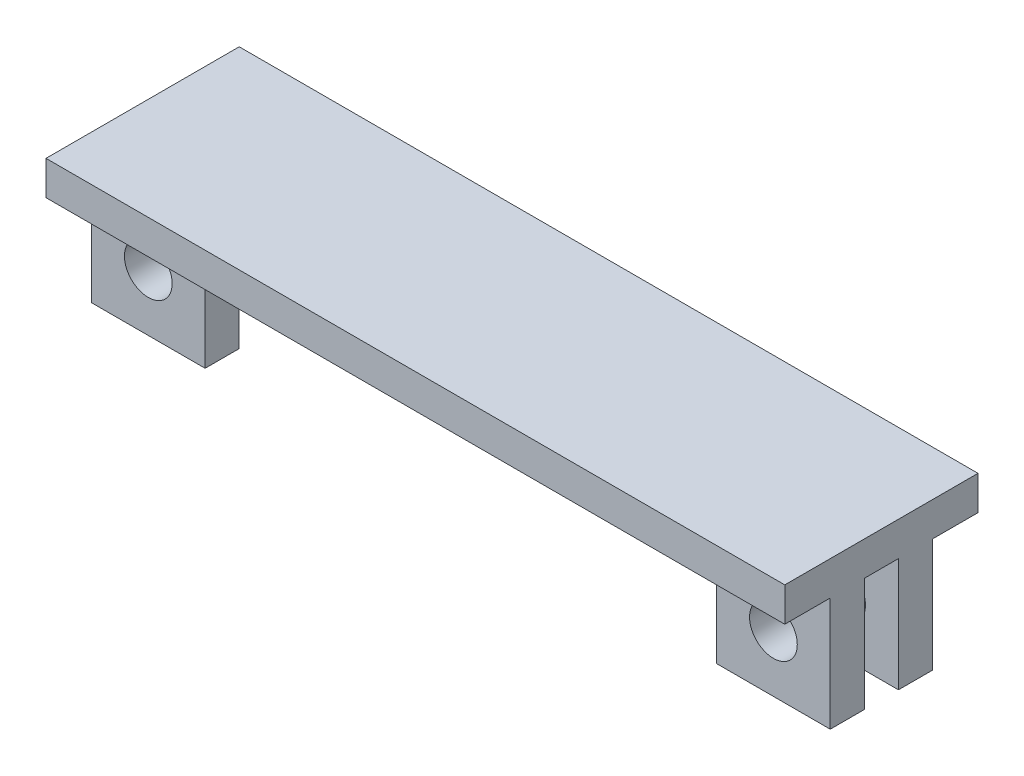
SolidWorks part; units mm, degrees
ref_plane "Спереди" through (0, 0, 0) normal (0, 0, 1) x (1, 0, 0)
ref_plane "Сверху" through (0, 0, 0) normal (0, 1, 0) x (1, 0, 0)
ref_plane "Справа" through (0, 0, 0) normal (1, 0, 0) x (0, 0, -1)
other "Configuration Table"
sketch "Эскиз3" plane through (0, 0, 0) normal (0, 1, 0) x (1, 0, 0)
  line L1 (-5, -1.5) -> (5, -1.5)
  line L2 (-5, -1.5) -> (-5, 1.5)
  line L3 (-5, 1.5) -> (5, 1.5)
  line L4 (5, -1.5) -> (5, 1.5)
  line L5 (-5, -1.5) -> (5, 1.5) construction
  line L6 (-5, 1.5) -> (5, -1.5) construction
  line L7 (50, -1.5) -> (60, -1.5)
  line L8 (50, -1.5) -> (50, 1.5)
  line L9 (50, 1.5) -> (60, 1.5)
  line L10 (60, -1.5) -> (60, 1.5)
  line L11 (50, -1.5) -> (60, 1.5) construction
  line L12 (50, 1.5) -> (60, -1.5) construction
  line L13 (-5, 4.5) -> (5, 4.5)
  line L14 (-5, 4.5) -> (-5, 7.5)
  line L15 (-5, 7.5) -> (5, 7.5)
  line L16 (5, 4.5) -> (5, 7.5)
  line L17 (-5, 4.5) -> (5, 7.5) construction
  line L18 (-5, 7.5) -> (5, 4.5) construction
  line L19 (50, 4.5) -> (60, 4.5)
  line L20 (50, 4.5) -> (50, 7.5)
  line L21 (50, 7.5) -> (60, 7.5)
  line L22 (60, 4.5) -> (60, 7.5)
  line L23 (50, 4.5) -> (60, 7.5) construction
  line L24 (50, 7.5) -> (60, 4.5) construction
  point P0 (0, 0)
  point P6 (55, 0)
  point P11 (0, 6)
  point P16 (55, 6)
  dimension "D1" = 3
  dimension "D2" = 10
  dimension "D3" = 10
  dimension "D4" = 3
  dimension "D5" = 55
  dimension "D6" = 55
  dimension "D7" = 3
extrude "Бобышка-Вытянуть1" add sketch "Эскиз3" along normal blind 10
sketch "Эскиз4" plane through (0, 10, 0) normal (0, 1, 0) x (1, 0, 0)
  line L1 (-5, 7.5) -> (60, 7.5)
  line L2 (-5, 7.5) -> (-5, -1.5)
  line L3 (-5, -1.5) -> (60, -1.5)
  line L4 (60, 7.5) -> (60, -1.5)
extrude "Бобышка-Вытянуть2" add sketch "Эскиз4" along normal blind 3
sketch "Эскиз5" plane through (0, 0, 1.5) normal (0, 0, 1) x (1, 0, 0)
  line L1 (50, 0) -> (60, 0) construction
  line L3 (50, 10) -> (50, 0) construction
  circle A0 centre (0, 5) radius 2.1
  circle A1 centre (55, 5) radius 2.1
  dimension "D1" = 4.2
  dimension "D2" = 4.2
  dimension "D3" = 5
  dimension "D4" = 5
  dimension "D5" = 5
extrude "Вырез-Вытянуть1" cut sketch "Эскиз5" against normal blind 17
sketch "Эскиз7" plane through (0, 0, -7.5) normal (0, 0, -1) x (-1, 0, 0)
  line L1 (-60, 13) -> (5, 13)
  line L2 (-60, 13) -> (-60, 10)
  line L3 (-60, 10) -> (5, 10)
  line L4 (5, 13) -> (5, 10)
extrude "Бобышка-Вытянуть3" add sketch "Эскиз7" along normal blind 4
sketch "Эскиз8" plane through (0, 0, 1.5) normal (0, 0, 1) x (1, 0, 0)
  line L1 (-5, 13) -> (60, 13)
  line L2 (-5, 13) -> (-5, 10)
  line L3 (-5, 10) -> (60, 10)
  line L4 (60, 13) -> (60, 10)
extrude "Бобышка-Вытянуть4" add sketch "Эскиз8" along normal blind 4
